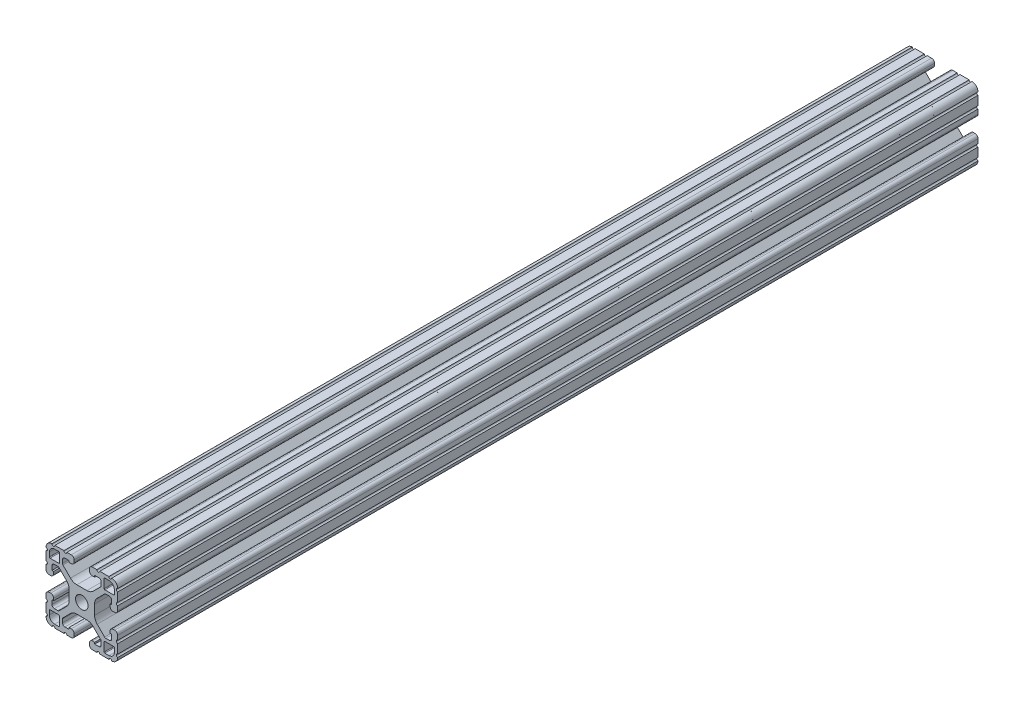
SolidWorks part; units mm, degrees
material "6061 Alloy"
ref_plane "Front Plane" through (0, 0, 0) normal (0, 0, 1) x (1, 0, 0)
ref_plane "Top Plane" through (0, 0, 0) normal (0, 1, 0) x (1, 0, 0)
ref_plane "Right Plane" through (0, 0, 0) normal (1, 0, 0) x (0, 0, -1)
sketch "Sketch1" plane through (0, 0, 0) normal (0, 0, 1) x (1, 0, 0)
  line L0 (0, 21.507) -> (0, -20.9529) construction
  line L1 (20.4424, 0) -> (-20.8151, 0) construction
  line L2 (10.0267, -12.1519) -> (6.0215, -8.1473)
  line L3 (-10.0267, 12.1519) -> (-6.0215, 8.1473)
  line L4 (-10.287, 14.5547) -> (-10.287, 12.7802)
  line L5 (-6.8141, 15.8247) -> (-9.017, 15.8247)
  line L6 (10.287, -14.5547) -> (10.287, -12.7802)
  line L7 (-6.8141, 14.986) -> (-6.8141, 15.8247)
  line L8 (6.8141, -15.8247) -> (9.017, -15.8247)
  line L9 (-2.6631, -6.7564) -> (2.6631, -6.7564)
  line L10 (6.8141, -14.986) -> (6.8141, -15.8247)
  line L11 (5.6388, -14.986) -> (6.8141, -14.986)
  line L12 (4.064, -17.4752) -> (4.064, -16.5608)
  line L13 (7.9756, -19.05) -> (5.6388, -19.05)
  line L14 (14.3256, -19.05) -> (9.4996, -19.05)
  line L15 (15.875, -19.05) -> (15.8496, -19.05)
  line L16 (19.05, -15.8496) -> (19.05, -15.875)
  line L17 (19.05, -9.4996) -> (19.05, -14.3256)
  line L18 (19.05, -5.6388) -> (19.05, -7.9756)
  line L19 (-5.6388, 14.986) -> (-6.8141, 14.986)
  line L20 (-4.064, 17.4752) -> (-4.064, 16.5608)
  line L21 (-7.9756, 19.05) -> (-5.6388, 19.05)
  line L22 (16.5608, -4.064) -> (17.4752, -4.064)
  line L23 (-14.3256, 19.05) -> (-9.4996, 19.05)
  line L24 (14.986, -6.7506) -> (14.986, -5.6388)
  line L25 (15.879, -6.7506) -> (14.986, -6.7506)
  line L26 (-15.875, 19.05) -> (-15.8496, 19.05)
  line L27 (-19.05, 15.8496) -> (-19.05, 15.875)
  line L28 (15.879, -8.9192) -> (15.879, -6.7506)
  line L29 (12.7428, -10.1892) -> (14.609, -10.1892)
  line L30 (-19.05, 9.4996) -> (-19.05, 14.3256)
  line L31 (-19.05, 5.6388) -> (-19.05, 7.9756)
  line L32 (8.1479, -5.9632) -> (12.1142, -9.9289)
  line L33 (16.891, -11.8618) -> (12.2428, -11.8618)
  line L34 (11.8618, -12.2428) -> (11.8618, -16.891)
  line L35 (12.2428, -17.272) -> (14.478, -17.272)
  line L36 (17.272, 14.478) -> (17.272, 12.2428)
  line L37 (12.2428, 17.272) -> (14.478, 17.272)
  line L38 (11.8618, 12.2428) -> (11.8618, 16.891)
  line L39 (16.891, 11.8618) -> (12.2428, 11.8618)
  line L40 (17.272, -14.478) -> (17.272, -12.2428)
  line L41 (-16.5608, 4.064) -> (-17.4752, 4.064)
  line L42 (-14.986, 6.7506) -> (-14.986, 5.6388)
  line L43 (-15.879, 6.7506) -> (-14.986, 6.7506)
  line L44 (-15.879, 8.9192) -> (-15.879, 6.7506)
  line L45 (-12.7428, 10.1892) -> (-14.609, 10.1892)
  line L46 (-8.1479, 5.9632) -> (-12.1142, 9.9289)
  line L47 (-6.7564, -2.6043) -> (-6.7564, 2.6043)
  line L48 (-17.272, -14.478) -> (-17.272, -12.2428)
  line L49 (-16.891, 11.8618) -> (-12.2428, 11.8618)
  line L50 (-11.8618, 12.2428) -> (-11.8618, 16.891)
  line L51 (-12.2428, 17.272) -> (-14.478, 17.272)
  line L52 (-17.272, 14.478) -> (-17.272, 12.2428)
  line L53 (-12.2428, -17.272) -> (-14.478, -17.272)
  line L54 (-11.8618, -12.2428) -> (-11.8618, -16.891)
  line L55 (-16.891, -11.8618) -> (-12.2428, -11.8618)
  line L56 (-8.1479, -5.9632) -> (-12.1142, -9.9289)
  line L57 (-12.7428, -10.1892) -> (-14.609, -10.1892)
  line L58 (-15.879, -8.9192) -> (-15.879, -6.7506)
  line L59 (-15.879, -6.7506) -> (-14.986, -6.7506)
  line L60 (-14.986, -6.7506) -> (-14.986, -5.6388)
  line L61 (-16.5608, -4.064) -> (-17.4752, -4.064)
  line L62 (-19.05, -5.6388) -> (-19.05, -7.9756)
  line L63 (-19.05, -9.4996) -> (-19.05, -14.3256)
  line L64 (-19.05, -15.8496) -> (-19.05, -15.875)
  line L65 (-15.875, -19.05) -> (-15.8496, -19.05)
  line L66 (-14.3256, -19.05) -> (-9.4996, -19.05)
  line L67 (-7.9756, -19.05) -> (-5.6388, -19.05)
  line L68 (-4.064, -17.4752) -> (-4.064, -16.5608)
  line L69 (-5.6388, -14.986) -> (-6.8141, -14.986)
  line L70 (-6.8141, -14.986) -> (-6.8141, -15.8247)
  line L71 (-6.8141, -15.8247) -> (-9.017, -15.8247)
  line L72 (-10.287, -14.5547) -> (-10.287, -12.7802)
  line L73 (-10.0267, -12.1519) -> (-6.0215, -8.1473)
  line L95 (6.7564, -2.6043) -> (6.7564, 2.6043)
  line L96 (8.1479, 5.9632) -> (12.1142, 9.9289)
  line L97 (12.7428, 10.1892) -> (14.609, 10.1892)
  line L98 (15.879, 8.9192) -> (15.879, 6.7506)
  line L99 (15.879, 6.7506) -> (14.986, 6.7506)
  line L100 (14.986, 6.7506) -> (14.986, 5.6388)
  line L101 (16.5608, 4.064) -> (17.4752, 4.064)
  line L102 (19.05, 5.6388) -> (19.05, 7.9756)
  line L103 (19.05, 9.4996) -> (19.05, 14.3256)
  line L104 (19.05, 15.8496) -> (19.05, 15.875)
  line L105 (15.875, 19.05) -> (15.8496, 19.05)
  line L106 (14.3256, 19.05) -> (9.4996, 19.05)
  line L107 (7.9756, 19.05) -> (5.6388, 19.05)
  line L108 (4.064, 17.4752) -> (4.064, 16.5608)
  line L109 (5.6388, 14.986) -> (6.8141, 14.986)
  line L110 (6.8141, 14.986) -> (6.8141, 15.8247)
  line L111 (6.8141, 15.8247) -> (9.017, 15.8247)
  line L112 (10.287, 14.5547) -> (10.287, 12.7802)
  line L113 (10.0267, 12.1519) -> (6.0215, 8.1473)
  line L114 (2.6631, 6.7564) -> (-2.6631, 6.7564)
  arc A0 (10.0267, -12.1519) -> (10.287, -12.7802) centre (9.3985, -12.7802) cw
  arc A1 (10.287, -14.5547) -> (9.017, -15.8247) centre (9.017, -14.5547) cw
  arc A2 (4.064, -16.5608) -> (5.6388, -14.986) centre (5.6388, -16.5608) cw
  arc A3 (-10.0267, 12.1519) -> (-10.287, 12.7802) centre (-9.3985, 12.7802) cw
  arc A4 (-10.287, 14.5547) -> (-9.017, 15.8247) centre (-9.017, 14.5547) cw
  arc A5 (5.6388, -19.05) -> (4.064, -17.4752) centre (5.6388, -17.4752) cw
  arc A6 (7.9756, -19.05) -> (9.4996, -19.05) centre (8.7376, -19.05) cw
  arc A7 (-4.064, 16.5608) -> (-5.6388, 14.986) centre (-5.6388, 16.5608) cw
  arc A8 (14.3256, -19.05) -> (15.8496, -19.05) centre (15.0876, -19.05) cw
  arc A9 (19.05, -15.875) -> (15.875, -19.05) centre (15.875, -15.875) cw
  arc A10 (6.0215, -8.1473) -> (2.6631, -6.7564) centre (2.6631, -11.5062) ccw
  arc A11 (-6.0215, -8.1473) -> (-2.6631, -6.7564) centre (-2.6631, -11.5062) cw
  arc A12 (19.05, -15.8496) -> (19.05, -14.3256) centre (19.05, -15.0876) cw
  arc A13 (19.05, -9.4996) -> (19.05, -7.9756) centre (19.05, -8.7376) cw
  arc A14 (17.4752, -4.064) -> (19.05, -5.6388) centre (17.4752, -5.6388) cw
  arc A15 (14.986, -5.6388) -> (16.5608, -4.064) centre (16.5608, -5.6388) cw
  arc A16 (15.879, -8.9192) -> (14.609, -10.1892) centre (14.609, -8.9192) cw
  arc A17 (12.7428, -10.1892) -> (12.1142, -9.9289) centre (12.7428, -9.3002) cw
  arc A18 (16.891, -11.8618) -> (17.272, -12.2428) centre (16.891, -12.2428) cw
  arc A19 (-5.6388, 19.05) -> (-4.064, 17.4752) centre (-5.6388, 17.4752) cw
  arc A20 (-7.9756, 19.05) -> (-9.4996, 19.05) centre (-8.7376, 19.05) cw
  arc A21 (-14.3256, 19.05) -> (-15.8496, 19.05) centre (-15.0876, 19.05) cw
  arc A22 (11.8618, -12.2428) -> (12.2428, -11.8618) centre (12.2428, -12.2428) cw
  arc A23 (-19.05, 15.875) -> (-15.875, 19.05) centre (-15.875, 15.875) cw
  arc A24 (12.2428, -17.272) -> (11.8618, -16.891) centre (12.2428, -16.891) cw
  arc A25 (17.272, -14.478) -> (14.478, -17.272) centre (14.478, -14.478) cw
  arc A26 (-19.05, 15.8496) -> (-19.05, 14.3256) centre (-19.05, 15.0876) cw
  arc A27 (-19.05, 9.4996) -> (-19.05, 7.9756) centre (-19.05, 8.7376) cw
  arc A28 (-17.4752, 4.064) -> (-19.05, 5.6388) centre (-17.4752, 5.6388) cw
  arc A29 (-14.986, 5.6388) -> (-16.5608, 4.064) centre (-16.5608, 5.6388) cw
  arc A30 (-15.879, 8.9192) -> (-14.609, 10.1892) centre (-14.609, 8.9192) cw
  arc A31 (-12.7428, 10.1892) -> (-12.1142, 9.9289) centre (-12.7428, 9.3002) cw
  arc A32 (-8.1479, 5.9632) -> (-6.7564, 2.6043) centre (-11.5062, 2.6043) cw
  arc A33 (-6.7564, -2.6043) -> (-8.1479, -5.9632) centre (-11.5062, -2.6043) cw
  arc A34 (-16.891, 11.8618) -> (-17.272, 12.2428) centre (-16.891, 12.2428) cw
  arc A35 (-11.8618, 12.2428) -> (-12.2428, 11.8618) centre (-12.2428, 12.2428) cw
  arc A36 (17.272, 14.478) -> (14.478, 17.272) centre (14.478, 14.478) ccw
  arc A37 (12.2428, 17.272) -> (11.8618, 16.891) centre (12.2428, 16.891) ccw
  arc A38 (11.8618, 12.2428) -> (12.2428, 11.8618) centre (12.2428, 12.2428) ccw
  arc A39 (16.891, 11.8618) -> (17.272, 12.2428) centre (16.891, 12.2428) ccw
  arc A40 (-12.2428, 17.272) -> (-11.8618, 16.891) centre (-12.2428, 16.891) cw
  circle A41 centre (0, 0) radius 3.3274
  arc A42 (-17.272, 14.478) -> (-14.478, 17.272) centre (-14.478, 14.478) cw
  arc A43 (-17.272, -14.478) -> (-14.478, -17.272) centre (-14.478, -14.478) ccw
  arc A44 (-12.2428, -17.272) -> (-11.8618, -16.891) centre (-12.2428, -16.891) ccw
  arc A45 (-11.8618, -12.2428) -> (-12.2428, -11.8618) centre (-12.2428, -12.2428) ccw
  arc A46 (-16.891, -11.8618) -> (-17.272, -12.2428) centre (-16.891, -12.2428) ccw
  arc A47 (-12.7428, -10.1892) -> (-12.1142, -9.9289) centre (-12.7428, -9.3002) ccw
  arc A48 (-15.879, -8.9192) -> (-14.609, -10.1892) centre (-14.609, -8.9192) ccw
  arc A49 (-14.986, -5.6388) -> (-16.5608, -4.064) centre (-16.5608, -5.6388) ccw
  arc A50 (-17.4752, -4.064) -> (-19.05, -5.6388) centre (-17.4752, -5.6388) ccw
  arc A51 (-19.05, -9.4996) -> (-19.05, -7.9756) centre (-19.05, -8.7376) ccw
  arc A52 (-19.05, -15.8496) -> (-19.05, -14.3256) centre (-19.05, -15.0876) ccw
  arc A53 (-19.05, -15.875) -> (-15.875, -19.05) centre (-15.875, -15.875) ccw
  arc A54 (-14.3256, -19.05) -> (-15.8496, -19.05) centre (-15.0876, -19.05) ccw
  arc A55 (-7.9756, -19.05) -> (-9.4996, -19.05) centre (-8.7376, -19.05) ccw
  arc A56 (-5.6388, -19.05) -> (-4.064, -17.4752) centre (-5.6388, -17.4752) ccw
  arc A57 (-4.064, -16.5608) -> (-5.6388, -14.986) centre (-5.6388, -16.5608) ccw
  arc A58 (-10.287, -14.5547) -> (-9.017, -15.8247) centre (-9.017, -14.5547) ccw
  arc A59 (-10.0267, -12.1519) -> (-10.287, -12.7802) centre (-9.3985, -12.7802) ccw
  arc A86 (6.7564, -2.6043) -> (8.1479, -5.9632) centre (11.5062, -2.6043) ccw
  arc A87 (8.1479, 5.9632) -> (6.7564, 2.6043) centre (11.5062, 2.6043) ccw
  arc A88 (12.7428, 10.1892) -> (12.1142, 9.9289) centre (12.7428, 9.3002) ccw
  arc A89 (15.879, 8.9192) -> (14.609, 10.1892) centre (14.609, 8.9192) ccw
  arc A90 (14.986, 5.6388) -> (16.5608, 4.064) centre (16.5608, 5.6388) ccw
  arc A91 (17.4752, 4.064) -> (19.05, 5.6388) centre (17.4752, 5.6388) ccw
  arc A92 (19.05, 9.4996) -> (19.05, 7.9756) centre (19.05, 8.7376) ccw
  arc A93 (19.05, 15.8496) -> (19.05, 14.3256) centre (19.05, 15.0876) ccw
  arc A94 (19.05, 15.875) -> (15.875, 19.05) centre (15.875, 15.875) ccw
  arc A95 (14.3256, 19.05) -> (15.8496, 19.05) centre (15.0876, 19.05) ccw
  arc A96 (7.9756, 19.05) -> (9.4996, 19.05) centre (8.7376, 19.05) ccw
  arc A97 (5.6388, 19.05) -> (4.064, 17.4752) centre (5.6388, 17.4752) ccw
  arc A98 (4.064, 16.5608) -> (5.6388, 14.986) centre (5.6388, 16.5608) ccw
  arc A99 (10.287, 14.5547) -> (9.017, 15.8247) centre (9.017, 14.5547) ccw
  arc A100 (10.0267, 12.1519) -> (10.287, 12.7802) centre (9.3985, 12.7802) ccw
  arc A101 (2.6631, 6.7564) -> (6.0215, 8.1473) centre (2.6631, 11.5062) ccw
  arc A102 (-6.0215, 8.1473) -> (-2.6631, 6.7564) centre (-2.6631, 11.5062) ccw
  dimension "D1" = 6.6548
  dimension "D2" = 38.1
  dimension "D3" = 20.574
  dimension "D4" = 12.2936
  dimension "D5" = 19.05
  dimension "D6" = 8.128
  dimension "D7" = 3.048
  dimension "D8" = 4.064
  dimension "D9" = 13.5128
extrude "Extrude1" add sketch "Sketch1" against normal blind 457.2
